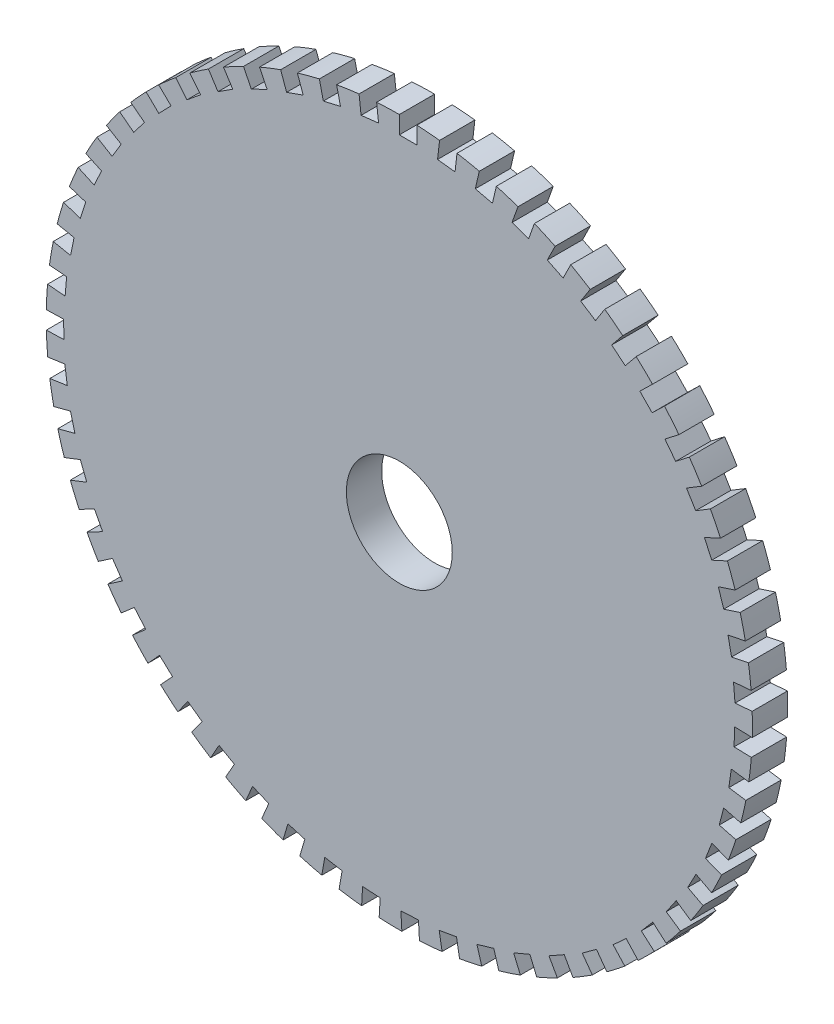
SolidWorks part; units mm, degrees
ref_plane "Front Plane" through (0, 0, 0) normal (0, 0, 1) x (1, 0, 0)
ref_plane "Top Plane" through (0, 0, 0) normal (0, 1, 0) x (1, 0, 0)
ref_plane "Right Plane" through (0, 0, 0) normal (1, 0, 0) x (0, 0, -1)
sketch "Sketch1" plane through (0, 0, 0) normal (0, 0, 1) x (1, 0, 0)
  circle A0 centre (0, 0) radius 10
  circle A1 centre (0, 0) radius 1.5
  dimension "D1" = 20
extrude "Boss-Extrude1" add sketch "Sketch1" along normal blind 1
sketch "Sketch2" plane through (0, 0, 1) normal (0, 0, 1) x (1, 0, 0)
  line L0 (1.0829, 9.4381) -> (1.1662, 10.1638)
  line L1 (0, 9.5) -> (0.4988, 9.5)
  line L2 (0, 9.5) -> (0, 10.2305)
  line L3 (0, 10.2305) -> (0.4988, 10.2305)
  line L4 (0.4988, 9.5) -> (0.4988, 10.2305)
  line L5 (1.0829, 9.4381) -> (1.5784, 9.3812)
  line L6 (1.5784, 9.3812) -> (1.6617, 10.107)
  line L7 (1.1662, 10.1638) -> (1.6617, 10.107)
  line L8 (2.1517, 9.2531) -> (2.3172, 9.9646)
  line L9 (2.1517, 9.2531) -> (2.6375, 9.1401)
  line L10 (2.6375, 9.1401) -> (2.803, 9.8517)
  line L11 (2.3172, 9.9646) -> (2.803, 9.8517)
  line L12 (3.1925, 8.9475) -> (3.438, 9.6356)
  line L13 (3.1925, 8.9475) -> (3.6622, 8.7799)
  line L14 (3.6622, 8.7799) -> (3.9077, 9.4679)
  line L15 (3.438, 9.6356) -> (3.9077, 9.4679)
  line L16 (4.1916, 8.5253) -> (4.5139, 9.1809)
  line L17 (4.1916, 8.5253) -> (4.6392, 8.3052)
  line L18 (4.6392, 8.3052) -> (4.9615, 8.9608)
  line L19 (4.5139, 9.1809) -> (4.9615, 8.9608)
  line L20 (5.1361, 7.9919) -> (5.531, 8.6065)
  line L21 (5.1361, 7.9919) -> (5.5557, 7.7223)
  line L22 (5.5557, 7.7223) -> (5.9506, 8.3368)
  line L23 (5.531, 8.6065) -> (5.9506, 8.3368)
  line L24 (6.0136, 7.3543) -> (6.476, 7.9199)
  line L25 (6.0136, 7.3543) -> (6.3997, 7.0386)
  line L26 (6.3997, 7.0386) -> (6.8622, 7.6041)
  line L27 (6.476, 7.9199) -> (6.8622, 7.6041)
  line L28 (6.8128, 6.6209) -> (7.3366, 7.13)
  line L29 (6.8128, 6.6209) -> (7.1604, 6.2632)
  line L30 (7.1604, 6.2632) -> (7.6842, 6.7723)
  line L31 (7.3366, 7.13) -> (7.6842, 6.7723)
  line L32 (7.5231, 5.8012) -> (8.1016, 6.2472)
  line L33 (7.5231, 5.8012) -> (7.8276, 5.4062)
  line L34 (7.8276, 5.4062) -> (8.4061, 5.8523)
  line L35 (8.1016, 6.2472) -> (8.4061, 5.8523)
  line L36 (8.1353, 4.9058) -> (8.7609, 5.283)
  line L37 (8.1353, 4.9058) -> (8.3929, 4.4787)
  line L38 (8.3929, 4.4787) -> (9.0185, 4.8559)
  line L39 (8.7609, 5.283) -> (9.0185, 4.8559)
  line L40 (8.6415, 3.9464) -> (9.306, 4.2499)
  line L41 (8.6415, 3.9464) -> (8.8487, 3.4927)
  line L42 (8.8487, 3.4927) -> (9.5132, 3.7962)
  line L43 (9.306, 4.2499) -> (9.5132, 3.7962)
  line L44 (9.035, 2.9357) -> (9.7298, 3.1614)
  line L45 (9.035, 2.9357) -> (9.1892, 2.4613)
  line L46 (9.1892, 2.4613) -> (9.8839, 2.687)
  line L47 (9.7298, 3.1614) -> (9.8839, 2.687)
  line L48 (9.3108, 1.8866) -> (10.0268, 2.0317)
  line L49 (9.3108, 1.8866) -> (9.4098, 1.3978)
  line L50 (9.4098, 1.3978) -> (10.1258, 1.5428)
  line L51 (10.0268, 2.0317) -> (10.1258, 1.5428)
  line L52 (9.4652, 0.813) -> (10.193, 0.8755)
  line L53 (9.4652, 0.813) -> (9.5078, 0.316)
  line L54 (9.5078, 0.316) -> (10.2357, 0.3785)
  line L55 (10.193, 0.8755) -> (10.2357, 0.3785)
  line L56 (9.4961, -0.2713) -> (10.2263, -0.2921)
  line L57 (9.4961, -0.2713) -> (9.4819, -0.7698)
  line L58 (9.4819, -0.7698) -> (10.2121, -0.7907)
  line L59 (10.2263, -0.2921) -> (10.2121, -0.7907)
  line L60 (9.4033, -1.352) -> (10.1264, -1.456)
  line L61 (9.4033, -1.352) -> (9.3323, -1.8457)
  line L62 (9.3323, -1.8457) -> (10.0554, -1.9496)
  line L63 (10.1264, -1.456) -> (10.0554, -1.9496)
  line L64 (9.1879, -2.4151) -> (9.8944, -2.6008)
  line L65 (9.1879, -2.4151) -> (9.0611, -2.8975)
  line L66 (9.0611, -2.8975) -> (9.7676, -3.0832)
  line L67 (9.8944, -2.6008) -> (9.7676, -3.0832)
  line L68 (8.8527, -3.4467) -> (9.5335, -3.7117)
  line L69 (8.8527, -3.4467) -> (8.6718, -3.9115)
  line L70 (8.6718, -3.9115) -> (9.3525, -4.1765)
  line L71 (9.5335, -3.7117) -> (9.3525, -4.1765)
  line L72 (8.4021, -4.4333) -> (9.0482, -4.7742)
  line L73 (8.4021, -4.4333) -> (8.1694, -4.8745)
  line L74 (8.1694, -4.8745) -> (8.8154, -5.2154)
  line L75 (9.0482, -4.7742) -> (8.8154, -5.2154)
  line L76 (7.842, -5.3622) -> (8.445, -5.7745)
  line L77 (7.842, -5.3622) -> (7.5605, -5.7739)
  line L78 (7.5605, -5.7739) -> (8.1635, -6.1863)
  line L79 (8.445, -5.7745) -> (8.1635, -6.1863)
  line L80 (7.1796, -6.2212) -> (7.7317, -6.6996)
  line L81 (7.1796, -6.2212) -> (6.853, -6.5981)
  line L82 (6.853, -6.5981) -> (7.4051, -7.0765)
  line L83 (7.7317, -6.6996) -> (7.4051, -7.0765)
  line L84 (6.4237, -6.999) -> (6.9176, -7.5372)
  line L85 (6.4237, -6.999) -> (6.0562, -7.3363)
  line L86 (6.0562, -7.3363) -> (6.5502, -7.8745)
  line L87 (6.9176, -7.5372) -> (6.5502, -7.8745)
  line L88 (5.584, -7.6857) -> (6.0133, -8.2767)
  line L89 (5.584, -7.6857) -> (5.1804, -7.9788)
  line L90 (5.1804, -7.9788) -> (5.6098, -8.5698)
  line L91 (6.0133, -8.2767) -> (5.6098, -8.5698)
  line L92 (4.6715, -8.2721) -> (5.0307, -8.9082)
  line L93 (4.6715, -8.2721) -> (4.2372, -8.5173)
  line L94 (4.2372, -8.5173) -> (4.5964, -9.1534)
  line L95 (5.0307, -8.9082) -> (4.5964, -9.1534)
  line L96 (3.6981, -8.7507) -> (3.9824, -9.4236)
  line L97 (3.6981, -8.7507) -> (3.2386, -8.9448)
  line L98 (3.2386, -8.9448) -> (3.523, -9.6177)
  line L99 (3.9824, -9.4236) -> (3.523, -9.6177)
  line L100 (2.6765, -9.1152) -> (2.8823, -9.8161)
  line L101 (2.6765, -9.1152) -> (2.1979, -9.2557)
  line L102 (2.1979, -9.2557) -> (2.4037, -9.9566)
  line L103 (2.8823, -9.8161) -> (2.4037, -9.9566)
  line L104 (1.62, -9.3609) -> (1.7445, -10.0807)
  line L105 (1.62, -9.3609) -> (1.1285, -9.4459)
  line L106 (1.1285, -9.4459) -> (1.2531, -10.1657)
  line L107 (1.7445, -10.0807) -> (1.2531, -10.1657)
  line L108 (0.5423, -9.4845) -> (0.584, -10.2138)
  line L109 (0.5423, -9.4845) -> (0.0444, -9.513)
  line L110 (0.0444, -9.513) -> (0.0861, -10.2423)
  line L111 (0.584, -10.2138) -> (0.0861, -10.2423)
  line L112 (-0.5423, -9.4845) -> (-0.584, -10.2138)
  line L113 (-0.5423, -9.4845) -> (-1.0403, -9.456)
  line L114 (-1.0403, -9.456) -> (-1.082, -10.1854)
  line L115 (-0.584, -10.2138) -> (-1.082, -10.1854)
  line L116 (-1.62, -9.3609) -> (-1.7445, -10.0807)
  line L117 (-1.62, -9.3609) -> (-2.1114, -9.2758)
  line L118 (-2.1114, -9.2758) -> (-2.236, -9.9956)
  line L119 (-1.7445, -10.0807) -> (-2.236, -9.9956)
  line L120 (-2.6765, -9.1152) -> (-2.8823, -9.8161)
  line L121 (-2.6765, -9.1152) -> (-3.155, -8.9747)
  line L122 (-3.155, -8.9747) -> (-3.3608, -9.6756)
  line L123 (-2.8823, -9.8161) -> (-3.3608, -9.6756)
  line L124 (-3.6981, -8.7507) -> (-3.9824, -9.4236)
  line L125 (-3.6981, -8.7507) -> (-4.1575, -8.5565)
  line L126 (-4.1575, -8.5565) -> (-4.4419, -9.2294)
  line L127 (-3.9824, -9.4236) -> (-4.4419, -9.2294)
  line L128 (-4.6715, -8.2721) -> (-5.0307, -8.9082)
  line L129 (-4.6715, -8.2721) -> (-5.1058, -8.0268)
  line L130 (-5.1058, -8.0268) -> (-5.465, -8.6629)
  line L131 (-5.0307, -8.9082) -> (-5.465, -8.6629)
  line L132 (-5.584, -7.6857) -> (-6.0133, -8.2767)
  line L133 (-5.584, -7.6857) -> (-5.9875, -7.3925)
  line L134 (-5.9875, -7.3925) -> (-6.4169, -7.9835)
  line L135 (-6.0133, -8.2767) -> (-6.4169, -7.9835)
  line L136 (-6.4237, -6.999) -> (-6.9176, -7.5372)
  line L137 (-6.4237, -6.999) -> (-6.7911, -6.6618)
  line L138 (-6.7911, -6.6618) -> (-7.2851, -7.2)
  line L139 (-6.9176, -7.5372) -> (-7.2851, -7.2)
  line L140 (-7.1796, -6.2212) -> (-7.7317, -6.6996)
  line L141 (-7.1796, -6.2212) -> (-7.5062, -5.8442)
  line L142 (-7.5062, -5.8442) -> (-8.0583, -6.3226)
  line L143 (-7.7317, -6.6996) -> (-8.0583, -6.3226)
  line L144 (-7.842, -5.3622) -> (-8.445, -5.7745)
  line L145 (-7.842, -5.3622) -> (-8.1235, -4.9505)
  line L146 (-8.1235, -4.9505) -> (-8.7265, -5.3628)
  line L147 (-8.445, -5.7745) -> (-8.7265, -5.3628)
  line L148 (-8.4021, -4.4333) -> (-9.0482, -4.7742)
  line L149 (-8.4021, -4.4333) -> (-8.6349, -3.9922)
  line L150 (-8.6349, -3.9922) -> (-9.281, -4.3331)
  line L151 (-9.0482, -4.7742) -> (-9.281, -4.3331)
  line L152 (-8.8527, -3.4467) -> (-9.5335, -3.7117)
  line L153 (-8.8527, -3.4467) -> (-9.0337, -2.9819)
  line L154 (-9.0337, -2.9819) -> (-9.7144, -3.2469)
  line L155 (-9.5335, -3.7117) -> (-9.7144, -3.2469)
  line L156 (-9.1879, -2.4151) -> (-9.8944, -2.6008)
  line L157 (-9.1879, -2.4151) -> (-9.3147, -1.9327)
  line L158 (-9.3147, -1.9327) -> (-10.0212, -2.1184)
  line L159 (-9.8944, -2.6008) -> (-10.0212, -2.1184)
  line L160 (-9.4033, -1.352) -> (-10.1264, -1.456)
  line L161 (-9.4033, -1.352) -> (-9.4743, -0.8583)
  line L162 (-9.4743, -0.8583) -> (-10.1974, -0.9623)
  line L163 (-10.1264, -1.456) -> (-10.1974, -0.9623)
  line L164 (-9.4961, -0.2713) -> (-10.2263, -0.2921)
  line L165 (-9.4961, -0.2713) -> (-9.5104, 0.2273)
  line L166 (-9.5104, 0.2273) -> (-10.2406, 0.2064)
  line L167 (-10.2263, -0.2921) -> (-10.2406, 0.2064)
  line L168 (-9.4652, 0.813) -> (-10.193, 0.8755)
  line L169 (-9.4652, 0.813) -> (-9.4225, 1.3099)
  line L170 (-9.4225, 1.3099) -> (-10.1503, 1.3724)
  line L171 (-10.193, 0.8755) -> (-10.1503, 1.3724)
  line L172 (-9.3108, 1.8866) -> (-10.0268, 2.0317)
  line L173 (-9.3108, 1.8866) -> (-9.2117, 2.3754)
  line L174 (-9.2117, 2.3754) -> (-9.9277, 2.5205)
  line L175 (-10.0268, 2.0317) -> (-9.9277, 2.5205)
  line L176 (-9.035, 2.9357) -> (-9.7298, 3.1614)
  line L177 (-9.035, 2.9357) -> (-8.8809, 3.41)
  line L178 (-8.8809, 3.41) -> (-9.5757, 3.6358)
  line L179 (-9.7298, 3.1614) -> (-9.5757, 3.6358)
  line L180 (-8.6415, 3.9464) -> (-9.306, 4.2499)
  line L181 (-8.6415, 3.9464) -> (-8.4343, 4.4001)
  line L182 (-8.4343, 4.4001) -> (-9.0988, 4.7036)
  line L183 (-9.306, 4.2499) -> (-9.0988, 4.7036)
  line L184 (-8.1353, 4.9058) -> (-8.7609, 5.283)
  line L185 (-8.1353, 4.9058) -> (-7.8778, 5.3329)
  line L186 (-7.8778, 5.3329) -> (-8.5033, 5.7101)
  line L187 (-8.7609, 5.283) -> (-8.5033, 5.7101)
  line L188 (-7.5231, 5.8012) -> (-8.1016, 6.2472)
  line L189 (-7.5231, 5.8012) -> (-7.2185, 6.1961)
  line L190 (-7.2185, 6.1961) -> (-7.797, 6.6422)
  line L191 (-8.1016, 6.2472) -> (-7.797, 6.6422)
  line L192 (-6.8128, 6.6209) -> (-7.3366, 7.13)
  line L193 (-6.8128, 6.6209) -> (-6.4651, 6.9786)
  line L194 (-6.4651, 6.9786) -> (-6.989, 7.4877)
  line L195 (-7.3366, 7.13) -> (-6.989, 7.4877)
  line L196 (-6.0136, 7.3543) -> (-6.476, 7.9199)
  line L197 (-6.0136, 7.3543) -> (-5.6275, 7.6701)
  line L198 (-5.6275, 7.6701) -> (-6.0899, 8.2356)
  line L199 (-6.476, 7.9199) -> (-6.0899, 8.2356)
  line L200 (-5.1361, 7.9919) -> (-5.531, 8.6065)
  line L201 (-5.1361, 7.9919) -> (-4.7165, 8.2616)
  line L202 (-4.7165, 8.2616) -> (-5.1114, 8.8761)
  line L203 (-5.531, 8.6065) -> (-5.1114, 8.8761)
  line L204 (-4.1916, 8.5253) -> (-4.5139, 9.1809)
  line L205 (-4.1916, 8.5253) -> (-3.744, 8.7454)
  line L206 (-3.744, 8.7454) -> (-4.0663, 9.4009)
  line L207 (-4.5139, 9.1809) -> (-4.0663, 9.4009)
  line L208 (-3.1925, 8.9475) -> (-3.438, 9.6356)
  line L209 (-3.1925, 8.9475) -> (-2.7227, 9.1151)
  line L210 (-2.7227, 9.1151) -> (-2.9682, 9.8032)
  line L211 (-3.438, 9.6356) -> (-2.9682, 9.8032)
  line L212 (-2.1517, 9.2531) -> (-2.3172, 9.9646)
  line L213 (-2.1517, 9.2531) -> (-1.6659, 9.3661)
  line L214 (-1.6659, 9.3661) -> (-1.8314, 10.0776)
  line L215 (-2.3172, 9.9646) -> (-1.8314, 10.0776)
  line L216 (-1.0829, 9.4381) -> (-1.1662, 10.1638)
  line L217 (-1.0829, 9.4381) -> (-0.5874, 9.4949)
  line L218 (-0.5874, 9.4949) -> (-0.6707, 10.2207)
  line L219 (-1.1662, 10.1638) -> (-0.6707, 10.2207)
  point P225 (0, 0)
  dimension "D2" = 55
extrude "Cut-Extrude1" cut sketch "Sketch2" against normal blind 1
